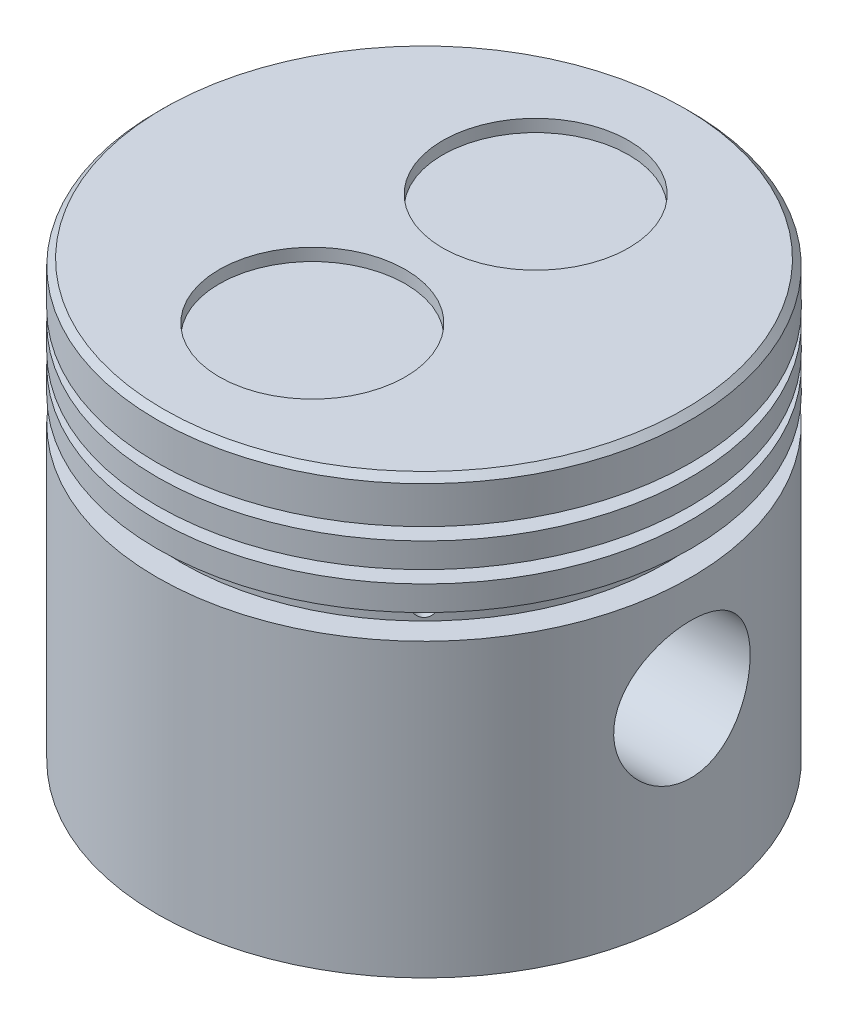
SolidWorks part; units mm, degrees
ref_plane "前视基准面" through (0, 0, 0) normal (0, 0, 1) x (1, 0, 0)
ref_plane "上视基准面" through (0, 0, 0) normal (0, 1, 0) x (1, 0, 0)
ref_plane "右视基准面" through (0, 0, 0) normal (1, 0, 0) x (0, 0, -1)
sketch "草图1" plane through (0, 0, 0) normal (0, 1, 0) x (1, 0, 0)
  circle A0 centre (0, 0) radius 43
extrude "凸台-拉伸1" add sketch "草图1" against normal blind 70
sketch "草图2" plane through (0, 0, 0) normal (0, 0, 1) x (1, 0, 0)
  line L0 (0, 0) -> (0, -70) construction
  line L1 (39, -9) -> (44, -9)
  line L2 (44, -9) -> (44, -7)
  line L3 (44, -7) -> (39, -7)
  line L4 (39, -7) -> (39, -9)
  line L5 (39, -15) -> (44, -15)
  line L6 (44, -15) -> (44, -13)
  line L7 (44, -13) -> (39, -13)
  line L8 (39, -13) -> (39, -15)
  line L9 (39, -23) -> (44, -23)
  line L10 (44, -23) -> (44, -19)
  line L11 (44, -19) -> (39, -19)
  line L12 (39, -19) -> (39, -23)
revolve "切除-旋转1" cut sketch "草图2" angle 360 about L0
ref_plane "基准面1" through (0, -70, 0) normal (0, 1, 0) x (1, 0, 0)
sketch "草图3" plane through (0, -70, 0) normal (0, 1, 0) x (1, 0, 0)
  circle A0 centre (0, 0) radius 37
extrude "切除-拉伸1" cut sketch "草图3" along normal blind 58
ref_plane "基准面2" through (22, 0, 0) normal (1, 0, 0) x (0, 0, -1)
sketch "草图4" plane through (22, 0, 0) normal (1, 0, 0) x (0, 0, -1)
  circle A0 centre (0, -40) radius 15
extrude "凸台-拉伸2" add sketch "草图4" along normal up to body
mirror "镜向1" about plane through (0, 0, 0) normal (1, 0, 0) of "凸台-拉伸2"
sketch "草图5" plane through (0, 0, 0) normal (1, 0, 0) x (0, 0, -1)
  circle A0 centre (0, -40) radius 11
extrude "切除-拉伸2" cut sketch "草图5" against normal mid plane 174
sketch "草图6" plane through (0, 0, 0) normal (0, 1, 0) x (1, 0, 0)
  circle A0 centre (0, -18) radius 15
  circle A1 centre (0, 18) radius 15
extrude "切除-拉伸3" cut sketch "草图6" against normal blind 2
ref_plane "基准面3" through (39, 0, 0) normal (1, 0, 0) x (0, 0, -1)
sketch "草图7" plane through (39, 0, 0) normal (1, 0, 0) x (0, 0, -1)
  circle A0 centre (0, -21) radius 1.5
extrude "切除-拉伸4" cut sketch "草图7" against normal blind 3.5
ref_axis "基准轴1" through (0, -73.5, 0) along (0, 1, 0)
pattern_circular "阵列(圆周)1" count 8 over 360 about axis through (0, -73.5, 0) along (0, 1, 0) of "切除-拉伸4"
chamfer "倒角1" distance 1 angle 45 1 edges at (0, 0, 43)
